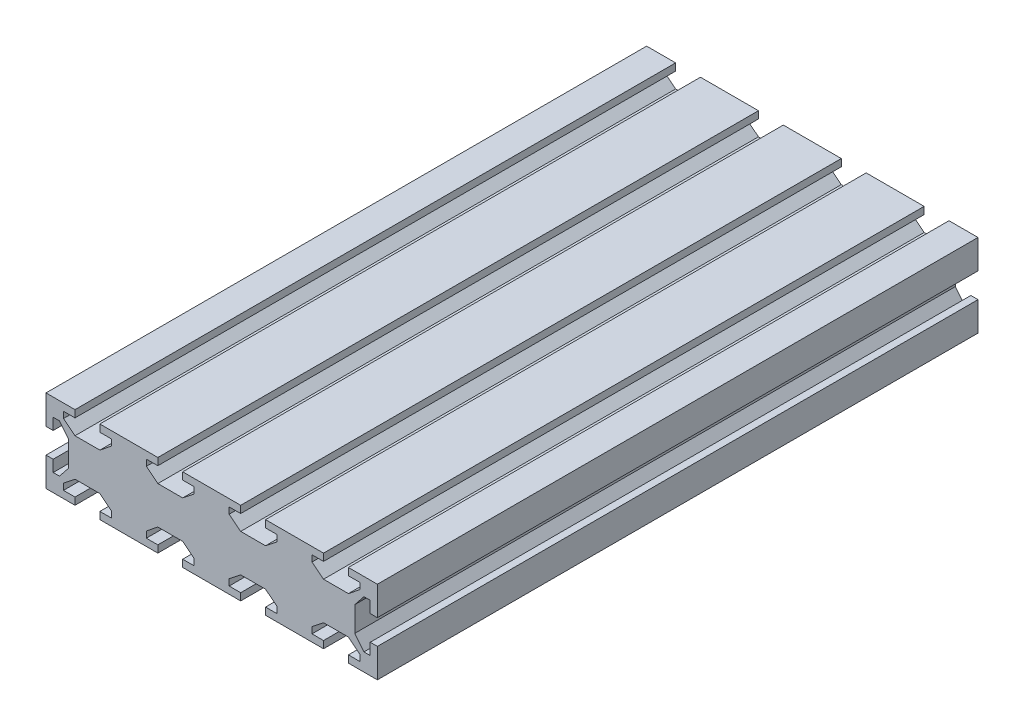
SolidWorks part; units mm, degrees
ref_plane "Front Plane" through (0, 0, 0) normal (0, 0, 1) x (1, 0, 0)
ref_plane "Top Plane" through (0, 0, 0) normal (0, 1, 0) x (1, 0, 0)
ref_plane "Right Plane" through (0, 0, 0) normal (1, 0, 0) x (0, 0, -1)
sketch "Sketch1" plane through (0, 0, 0) normal (0, 0, 1) x (1, 0, 0)
  line L0 (-10, 3) -> (-10, 10)
  line L1 (-10, 10) -> (-3, 10)
  line L2 (-3, 10) -> (-3, 8.27)
  line L3 (-10, 3) -> (-8.27, 3)
  line L4 (-3, 8.27) -> (-5.78, 8.27)
  line L5 (-8.27, 3) -> (-8.27, 5.78)
  line L6 (-5.78, 8.27) -> (-5.78, 6.75)
  line L7 (-8.27, 5.78) -> (-6.75, 5.78)
  line L8 (-5.78, 6.75) -> (-3, 4.5423)
  line L9 (-6.75, 5.78) -> (-4.5423, 3)
  line L10 (-3, 4.5423) -> (3, 4.5423)
  line L11 (-4.5423, 3) -> (-4.5423, -3)
  line L12 (0, 0) -> (-4.5423, 0) construction
  line L13 (-3, -4.5423) -> (3, -4.5423)
  line L14 (-6.75, -5.78) -> (-4.5423, -3)
  line L15 (-5.78, -6.75) -> (-3, -4.5423)
  line L16 (-8.27, -5.78) -> (-6.75, -5.78)
  line L17 (-5.78, -8.27) -> (-5.78, -6.75)
  line L18 (-8.27, -3) -> (-8.27, -5.78)
  line L19 (-3, -8.27) -> (-5.78, -8.27)
  line L20 (-10, -3) -> (-8.27, -3)
  line L21 (-3, -10) -> (-3, -8.27)
  line L22 (-10, -10) -> (-3, -10)
  line L23 (-10, -3) -> (-10, -10)
  line L24 (0, 4.5423) -> (0, -4.5423) construction
  line L25 (5.78, 6.75) -> (3, 4.5423)
  line L26 (5.78, 8.27) -> (5.78, 6.75)
  line L27 (5.78, -6.75) -> (3, -4.5423)
  line L28 (5.78, -8.27) -> (5.78, -6.75)
  line L29 (3, -8.27) -> (5.78, -8.27)
  line L30 (3, 8.27) -> (5.78, 8.27)
  line L31 (10, -10) -> (3, -10)
  line L32 (3, -10) -> (3, -8.27)
  line L33 (3, 10) -> (3, 8.27)
  line L34 (10, 10) -> (3, 10)
  line L35 (17, 10) -> (17, 8.27)
  line L36 (17, 8.27) -> (14.22, 8.27)
  line L37 (14.22, 8.27) -> (14.22, 6.75)
  line L38 (14.22, 6.75) -> (17, 4.5423)
  line L39 (17, 4.5423) -> (23, 4.5423)
  line L40 (17, -4.5423) -> (23, -4.5423)
  line L41 (14.22, -6.75) -> (17, -4.5423)
  line L42 (14.22, -8.27) -> (14.22, -6.75)
  line L43 (17, -8.27) -> (14.22, -8.27)
  line L44 (17, -10) -> (17, -8.27)
  line L45 (25.78, 6.75) -> (23, 4.5423)
  line L46 (25.78, 8.27) -> (25.78, 6.75)
  line L47 (25.78, -6.75) -> (23, -4.5423)
  line L48 (25.78, -8.27) -> (25.78, -6.75)
  line L49 (23, -8.27) -> (25.78, -8.27)
  line L50 (23, 8.27) -> (25.78, 8.27)
  line L51 (30, -10) -> (23, -10)
  line L52 (23, -10) -> (23, -8.27)
  line L53 (23, 10) -> (23, 8.27)
  line L54 (30, 10) -> (23, 10)
  line L55 (30, 10) -> (30, -10) construction
  line L56 (10, -10) -> (17, -10)
  line L57 (10, 10) -> (17, 10)
  line L58 (37, 10) -> (37, 8.27)
  line L59 (37, 8.27) -> (34.22, 8.27)
  line L60 (34.22, 8.27) -> (34.22, 6.75)
  line L61 (34.22, 6.75) -> (37, 4.5423)
  line L62 (37, 4.5423) -> (43, 4.5423)
  line L63 (37, -4.5423) -> (43, -4.5423)
  line L64 (34.22, -6.75) -> (37, -4.5423)
  line L65 (34.22, -8.27) -> (34.22, -6.75)
  line L66 (37, -8.27) -> (34.22, -8.27)
  line L67 (37, -10) -> (37, -8.27)
  line L68 (45.78, 6.75) -> (43, 4.5423)
  line L69 (45.78, 8.27) -> (45.78, 6.75)
  line L70 (45.78, -6.75) -> (43, -4.5423)
  line L71 (45.78, -8.27) -> (45.78, -6.75)
  line L72 (43, -8.27) -> (45.78, -8.27)
  line L73 (43, 8.27) -> (45.78, 8.27)
  line L74 (50, -10) -> (43, -10)
  line L75 (43, -10) -> (43, -8.27)
  line L76 (43, 10) -> (43, 8.27)
  line L77 (50, 10) -> (43, 10)
  line L78 (70, 10) -> (70, 3)
  line L79 (30, -10) -> (37, -10)
  line L80 (30, 10) -> (37, 10)
  line L81 (57, 10) -> (57, 8.27)
  line L82 (57, 8.27) -> (54.22, 8.27)
  line L83 (54.22, 8.27) -> (54.22, 6.75)
  line L84 (54.22, 6.75) -> (57, 4.5423)
  line L85 (57, 4.5423) -> (63, 4.5423)
  line L86 (57, -4.5423) -> (63, -4.5423)
  line L87 (54.22, -6.75) -> (57, -4.5423)
  line L88 (54.22, -8.27) -> (54.22, -6.75)
  line L89 (57, -8.27) -> (54.22, -8.27)
  line L90 (57, -10) -> (57, -8.27)
  line L91 (65.78, 6.75) -> (63, 4.5423)
  line L92 (65.78, 8.27) -> (65.78, 6.75)
  line L93 (65.78, -6.75) -> (63, -4.5423)
  line L94 (65.78, -8.27) -> (65.78, -6.75)
  line L95 (63, -8.27) -> (65.78, -8.27)
  line L96 (63, 8.27) -> (65.78, 8.27)
  line L97 (70, -10) -> (63, -10)
  line L98 (63, -10) -> (63, -8.27)
  line L99 (63, 10) -> (63, 8.27)
  line L100 (70, 10) -> (63, 10)
  line L101 (70, 3) -> (68.27, 3)
  line L102 (50, -10) -> (57, -10)
  line L103 (50, 10) -> (57, 10)
  line L104 (20, 0) -> (15.4577, 0) construction
  line L105 (40, 0) -> (35.4577, 0) construction
  line L106 (60, 0) -> (55.4577, 0) construction
  line L107 (68.27, 3) -> (68.27, 5.78)
  line L108 (68.27, 5.78) -> (66.75, 5.78)
  line L109 (66.75, 5.78) -> (64.5423, 3)
  line L110 (64.5423, 3) -> (64.5423, -3)
  line L111 (64.5423, -3) -> (66.75, -5.78)
  line L112 (66.75, -5.78) -> (68.27, -5.78)
  line L113 (68.27, -5.78) -> (68.27, -3)
  line L114 (68.27, -3) -> (70, -3)
  line L115 (70, -3) -> (70, -10)
  dimension "D1" = 7
  dimension "D2" = 1.73
  dimension "D3" = 2.78
  dimension "D4" = 10
  dimension "D5" = 10
  dimension "D6" = 1.52
  dimension "D7" = 3.55
  dimension "D8" = 3
  dimension "D9" = 3
  dimension "D10" = 3
  dimension "D12" = 17
  dimension "D11" = 4
extrude "Boss-Extrude1" add sketch "Sketch1" along normal mid plane 145
